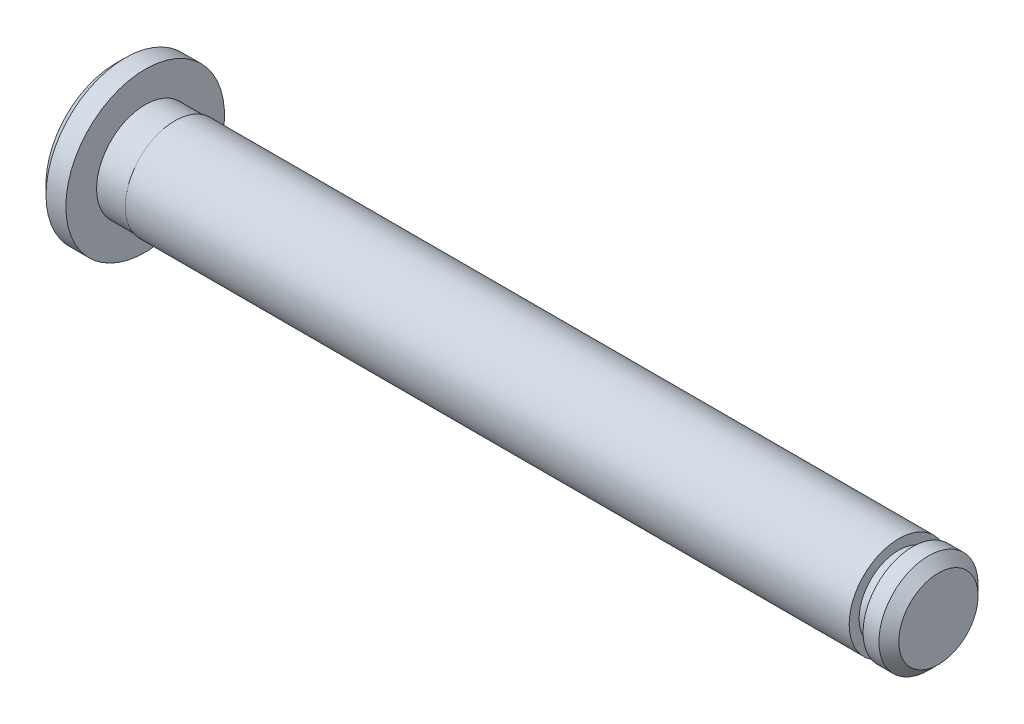
SolidWorks part; units mm, degrees
ref_plane "Front Plane" through (0, 0, 0) normal (0, 0, 1) x (1, 0, 0)
ref_plane "Top Plane" through (0, 0, 0) normal (0, 1, 0) x (1, 0, 0)
ref_plane "Right Plane" through (0, 0, 0) normal (1, 0, 0) x (0, 0, -1)
sketch "Sketch1" plane through (0, 0, 0) normal (0, 0, 1) x (1, 0, 0)
  line L0 (0, 0) -> (40, 0) construction
  line L1 (-1.5, 0) -> (-1.5, 4)
  line L2 (-1.5, 4) -> (0, 4)
  line L3 (0, 4) -> (0, 2.45)
  line L4 (0, 2.45) -> (1.5, 2.45)
  line L5 (40, 2.5) -> (40, 0)
  line L6 (-1.5, 0) -> (40, 0)
  line L7 (1.5, 2.45) -> (1.5, 2.5)
  line L8 (1.5, 2.5) -> (38, 2.5)
  line L9 (38, 2.5) -> (38, 2)
  line L10 (38, 2) -> (38.7, 2)
  line L11 (38.7, 2) -> (38.7, 2.5)
  line L12 (38.7, 2.5) -> (40, 2.5)
  dimension "L" = 38
  dimension "D_s" = 4
  dimension "H" = 8
  dimension "T" = 1.5
  dimension "N_s" = 1.5
  dimension "U_s" = 4.9
  dimension "M" = 0.7
  dimension "N" = 2
  dimension "D" = 5
revolve "Revolve1" add sketch "Sketch1" angle 360 about L0
chamfer "Chamfer1" distance 0.5 angle 45 2 edges at (-1.5, 0, 4) (40, 0, 2.5)
sketch "Sketch2" [suppressed] plane through (0, 0, 0) normal (0, 0, 1) x (1, 0, 0)
  line L0 (-1.5, 2.25) -> (-1.5, -2.25) construction
  line L3 (0, 0) -> (12, 0)
  line L4 (0, 0) -> (0, 1.5)
  line L5 (0, 1.5) -> (12, 1.5)
  line L6 (-1.5, 0) -> (12, 0) construction
  line L7 (12, -1) -> (12, 1) construction
  line L9 (12, 0) -> (12, 1.5)
  dimension "D" = 5
revolve "Cut-Revolve1" [suppressed] cut sketch "Sketch2" angle 360 about L6
sketch "Sketch3" [suppressed] plane through (0, 0, 0) normal (0, 0, 1) x (1, 0, 0)
  line L0 (0, 0) -> (11.5, 0) construction
  line L1 (0, -2.75) -> (0, 2.75) construction
  line L3 (0, 0) -> (0, 1.45)
  line L4 (0, 1.45) -> (1.5, 1.45)
  line L5 (11.5, 1.5) -> (11.5, 0)
  line L6 (0, 0) -> (11.5, 0)
  line L7 (1.5, 1.45) -> (1.5, 1.5)
  line L8 (1.5, 1.5) -> (10, 1.5)
  line L9 (10, 1.5) -> (10, 1)
  line L10 (10, 1) -> (10.5, 1)
  line L11 (10.5, 1) -> (10.5, 1.5)
  line L12 (10.5, 1.5) -> (11.5, 1.5)
  dimension "D" = 5
  dimension "L" = 38
  dimension "D_s" = 4
  dimension "N_s" = 1.5
  dimension "U_s" = 4.9
  dimension "M" = 0.7
  dimension "NC" = 1.5
revolve "Revolve2" [suppressed] add sketch "Sketch3" angle 360 about L0
chamfer "Chamfer2" [suppressed] distance 0.5 angle 45
sketch "Sketch4" [suppressed] plane through (0, 0, 0) normal (0, 0, 1) x (1, 0, 0)
  line L0 (-1.5, 2.25) -> (-1.5, -2.25) construction
  line L1 (-1.5, 2.75) -> (0, 2.75)
  line L2 (-1.5, 2.75) -> (-1.5, 0)
  line L3 (-1.5, 0) -> (0, 0)
  line L4 (0, 2.75) -> (0, 0)
  line L6 (0, -2.75) -> (0, 2.75) construction
  line L7 (0, 0) -> (-1.5, 0) construction
  dimension "H" = 8
revolve "Cut-Revolve2" [suppressed] cut sketch "Sketch4" angle 360 about L7
sketch "Sketch5" [suppressed] plane through (0, 0, 0) normal (0, 0, 1) x (1, 0, 0)
  line L1 (-2, 2.75) -> (0, 2.75)
  line L2 (-2, 2.75) -> (-2, 0)
  line L3 (-2, 0) -> (0, 0)
  line L4 (0, 2.75) -> (0, 0)
  line L7 (0, 0) -> (-2, 0) construction
  dimension "TC" = 2
  dimension "H" = 8
revolve "Revolve3" [suppressed] add sketch "Sketch5" angle 360 about L7
chamfer "Chamfer3" [suppressed] distance 0.5 angle 45
sketch "Sketch6" [suppressed] plane through (0, 0, 0) normal (1, 0, 0) x (0, 0, -1)
  line L0 (0, 0) -> (-2.75, 0) construction
  line L1 (-2.75, 2.75) -> (-1.75, 2.75)
  line L2 (-2.75, 2.75) -> (-2.75, -2.75)
  line L3 (-2.75, -2.75) -> (-1.75, -2.75)
  line L4 (-1.75, 2.75) -> (-1.75, -2.75)
  dimension "D2" = 4
  dimension "HC" = 3
  dimension "H" = 8
extrude "Cut-Extrude1" [suppressed] cut sketch "Sketch6" against normal through all
equation "\"D2@Sketch6\" = \"H@Sketch1\" / 2"
equation "\"HC@Sketch6\"=if ( \"D@Sketch1\" > 10 , \"H@Sketch1\" / 2 - 2 , \"H@Sketch1\" / 2 - 1 )"
